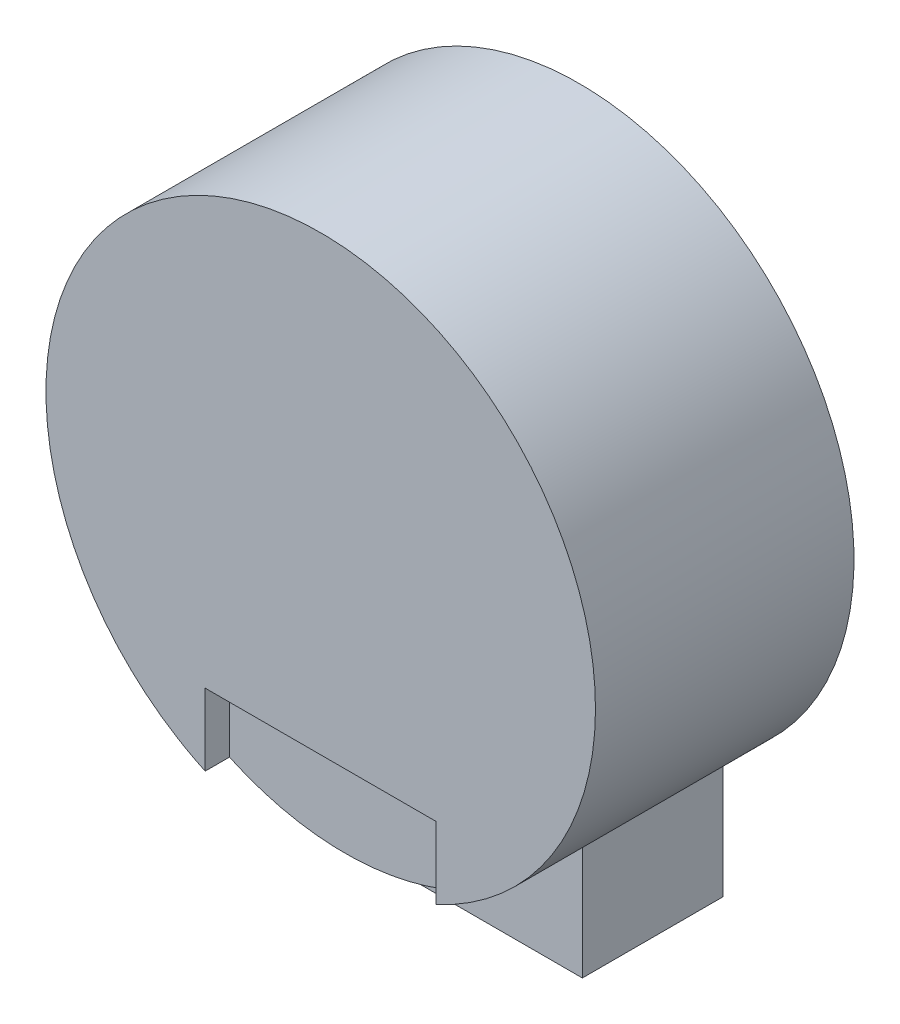
SolidWorks part; units mm, degrees
ref_plane "Přední rovina" through (0, 0, 0) normal (0, 0, 1) x (1, 0, 0)
ref_plane "Horní rovina" through (0, 0, 0) normal (0, 1, 0) x (1, 0, 0)
ref_plane "Pravá rovina" through (0, 0, 0) normal (1, 0, 0) x (0, 0, -1)
sketch "Skica1" plane through (0, 0, 0) normal (0, 0, 1) x (1, 0, 0)
  line L1 (-2.3, -5.731) -> (2.3, -5.731)
  line L2 (-2.3, -5.731) -> (-2.3, -3.751)
  line L3 (1.5895, -3.5975) -> (1.6239, -3.5975)
  line L4 (2.3, -5.731) -> (2.3, -3.751)
  line L5 (-2.3, -5.731) -> (0, -4.4) construction
  line L6 (0, -4.4) -> (2.3, -5.731) construction
  circle A0 centre (0, 0) radius 4.4
  point P3 (0, -4.4)
  dimension "D1" = 8.8
  dimension "D2" = 1.98
  dimension "D3" = 4.6
extrude "Přidat vysunutím1" add sketch "Skica1" along normal blind 2.25
sketch "Skica2" plane through (0, -5.731, 0) normal (0, -1, 0) x (-1, 0, 0)
  line L0 (2.3, 0) -> (-2.3, 0) construction
  line L1 (-1.75, -1.2) -> (1.75, -1.2)
  line L2 (-1.75, -1.2) -> (-1.75, -0.7)
  line L3 (-1.75, -0.7) -> (1.75, -0.7)
  line L4 (1.75, -1.2) -> (1.75, -0.7)
  line L5 (-1.75, -1.2) -> (1.75, -0.7) construction
  line L6 (-1.75, -0.7) -> (1.75, -1.2) construction
  line L8 (2.3, -2.25) -> (2.3, 0) construction
  line L9 (-2.3, -2.25) -> (-2.3, 0) construction
  point P0 (0, -0.95)
  dimension "D1" = 0.7
  dimension "D2" = 0.5
  dimension "D3" = 0.55
  dimension "D4" = 0.55
extrude "Odebrat vysunutím1" cut sketch "Skica2" against normal blind 3.2891
sketch "Skica3" plane through (0, 0, 2.25) normal (0, 0, 1) x (1, 0, 0)
  circle A0 centre (0, 0) radius 4.4
  arc A1 (2.3, -3.751) -> (-2.3, -3.751) centre (0, 0) ccw construction
extrude "Přidat vysunutím2" add sketch "Skica3" along normal blind 1.89
ref_plane "Rovina1" through (0, -5.731, 0) normal (0, -1, 0) x (-1, 0, 0)
sketch "Skica5" plane through (0, -5.731, 0) normal (0, -1, 0) x (-1, 0, 0)
  line L0 (0, -1.2) -> (0, -5.0394) construction
  line L1 (-1.85, -5.0394) -> (1.85, -5.0394)
  line L2 (-1.85, -5.0394) -> (-1.85, -3.7513)
  line L3 (-1.85, -3.7513) -> (1.85, -3.7513)
  line L4 (1.85, -5.0394) -> (1.85, -3.7513)
  line L5 (-1.85, -5.0394) -> (1.85, -3.7513) construction
  line L6 (-1.85, -3.7513) -> (1.85, -5.0394) construction
  line L7 (-1.75, -1.2) -> (1.75, -1.2) construction
  point P0 (0, -4.3954)
  dimension "D1" = 3.7
extrude "Odebrat vysunutím2" cut sketch "Skica5" against normal blind 2.89
